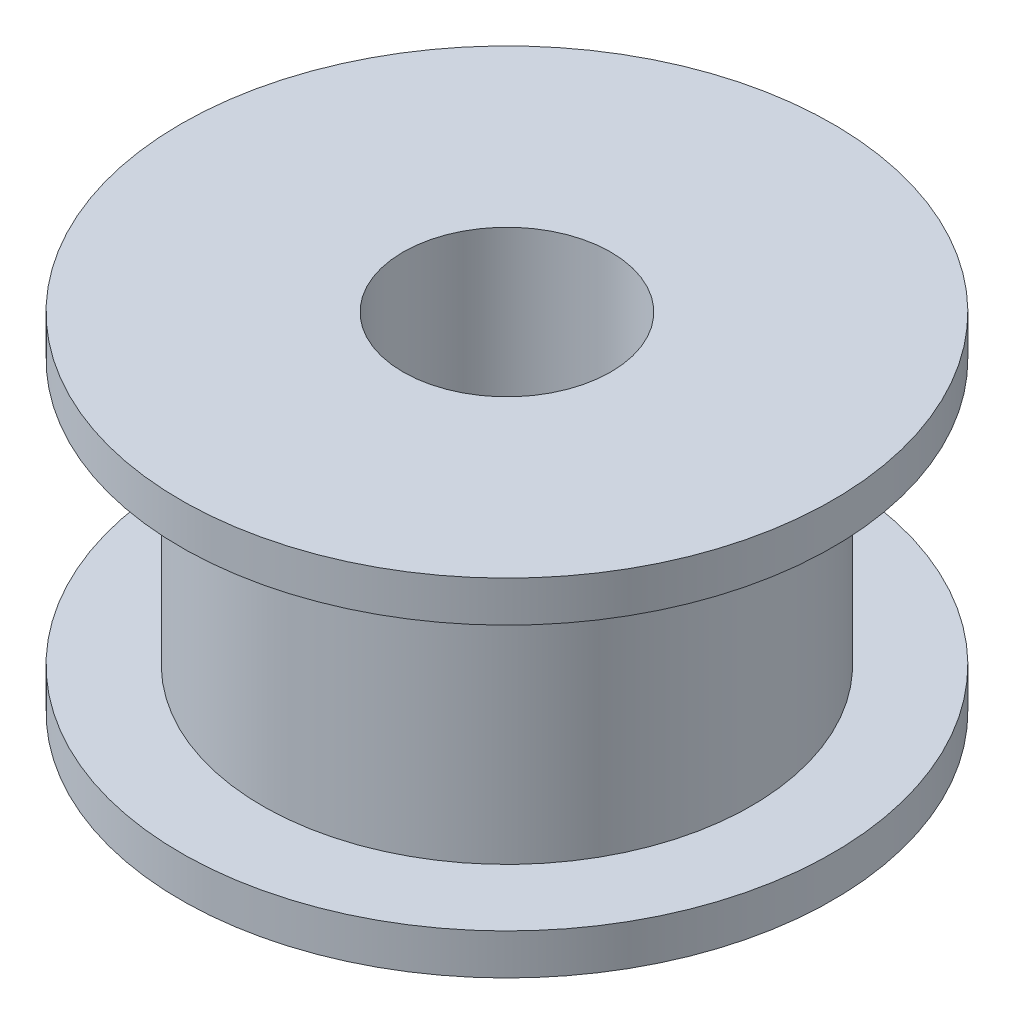
SolidWorks part; units mm, degrees
ref_plane "Front Plane" through (0, 0, 0) normal (0, 0, 1) x (1, 0, 0)
ref_plane "Top Plane" through (0, 0, 0) normal (0, 1, 0) x (1, 0, 0)
ref_plane "Right Plane" through (0, 0, 0) normal (1, 0, 0) x (0, 0, -1)
sketch "Sketch1" plane through (0, 0, 0) normal (0, 0, 1) x (1, 0, 0)
  line L0 (0, 0) -> (-8, 0)
  line L1 (-8, 0) -> (-8, 1)
  line L2 (-8, 1) -> (-6, 1)
  line L3 (-6, 1) -> (-6, 7.5)
  line L4 (-6, 7.5) -> (-8, 7.5)
  line L5 (-8, 7.5) -> (-8, 8.5)
  line L6 (-8, 8.5) -> (0, 8.5)
  line L7 (0, 8.5) -> (0, 0)
  dimension "D1" = 8
  dimension "D2" = 1
  dimension "D3" = 1
  dimension "D4" = 8.5
  dimension "D5" = 6
  dimension "D6" = 8
revolve "Revolve1" add sketch "Sketch1" angle 360 about L7
sketch "Sketch2" plane through (0, 8.5, 0) normal (0, 1, 0) x (1, 0, 0)
  circle A0 centre (0, 0) radius 2.55
  dimension "D1" = 5.1
extrude "Cut-Extrude1" cut sketch "Sketch2" against normal through all
